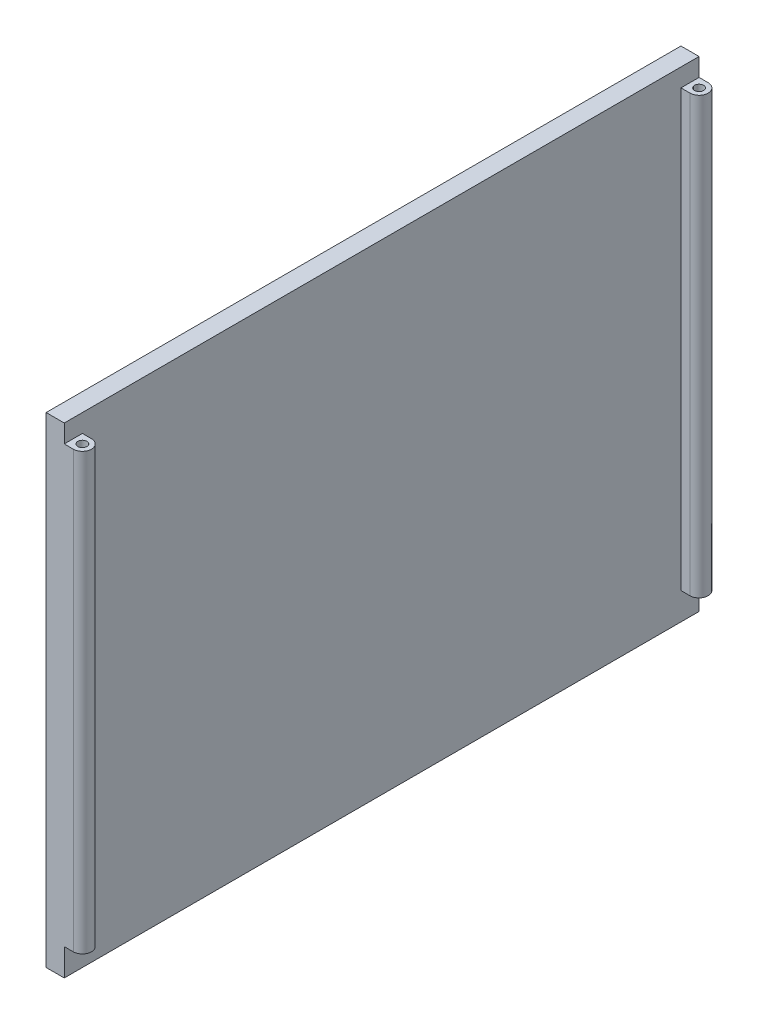
SolidWorks part; units mm, degrees
ref_plane "Спереди" through (0, 0, 0) normal (0, 0, 1) x (1, 0, 0)
ref_plane "Сверху" through (0, 0, 0) normal (0, 1, 0) x (1, 0, 0)
ref_plane "Справа" through (0, 0, 0) normal (1, 0, 0) x (0, 0, -1)
sketch "Эскиз1" plane through (0, 0, 0) normal (1, 0, 0) x (0, 0, -1)
  line L0 (0, 50) -> (0, -50) construction
  line L1 (-35, 53) -> (35, 53)
  line L2 (-35, 53) -> (-35, 0)
  line L3 (-35, 0) -> (35, 0)
  line L4 (35, 53) -> (35, 0)
  line L5 (50, 0) -> (-50, 0) construction
  point P4 (0, 53)
  dimension "D1" = 70
  dimension "D2" = 53
extrude "Бобышка-Вытянуть1" add sketch "Эскиз1" along normal blind 2
sketch "Эскиз2" plane through (0, 0, 0) normal (0, 1, 0) x (1, 0, 0)
  line L0 (2, -35) -> (2, 35) construction
  line L1 (2, 35) -> (0, 35) construction
  line L2 (2, 35) -> (3, 35)
  line L3 (2, 35) -> (0, 35) construction
  line L4 (2, 33) -> (2, 35)
  line L5 (2, 33) -> (3, 33)
  circle A0 centre (3, 34) radius 0.5
  arc A1 (3, 33) -> (3, 35) centre (3, 34) ccw
  dimension "D1" = 1
  dimension "D2" = 2
  dimension "D3" = 1
extrude "Бобышка-Вытянуть2" add sketch "Эскиз2" along normal blind 48 from offset 3
mirror "Зеркальное отражение1" about plane through (0, 0, 0) normal (0, 0, 1) of "Бобышка-Вытянуть2"
sketch "Эскиз3" plane through (0, 0, 0) normal (0, 0, 1) x (1, 0, 0)
  line L0 (0, -50) -> (0, 50) construction
  line L1 (-1, 29) -> (0, 29)
  line L3 (0, 29) -> (0, 27)
  line L4 (0, 27) -> (-1, 27)
  line L5 (50, 0) -> (-50, 0) construction
  circle A0 centre (-1, 28) radius 0.5
  arc A1 (-1, 29) -> (-1, 27) centre (-1, 28) ccw
  dimension "D1" = 1
  dimension "D2" = 1
  dimension "D3" = 2
  dimension "D4" = 28
extrude "Бобышка-Вытянуть3" add sketch "Эскиз3" along normal mid plane 5
